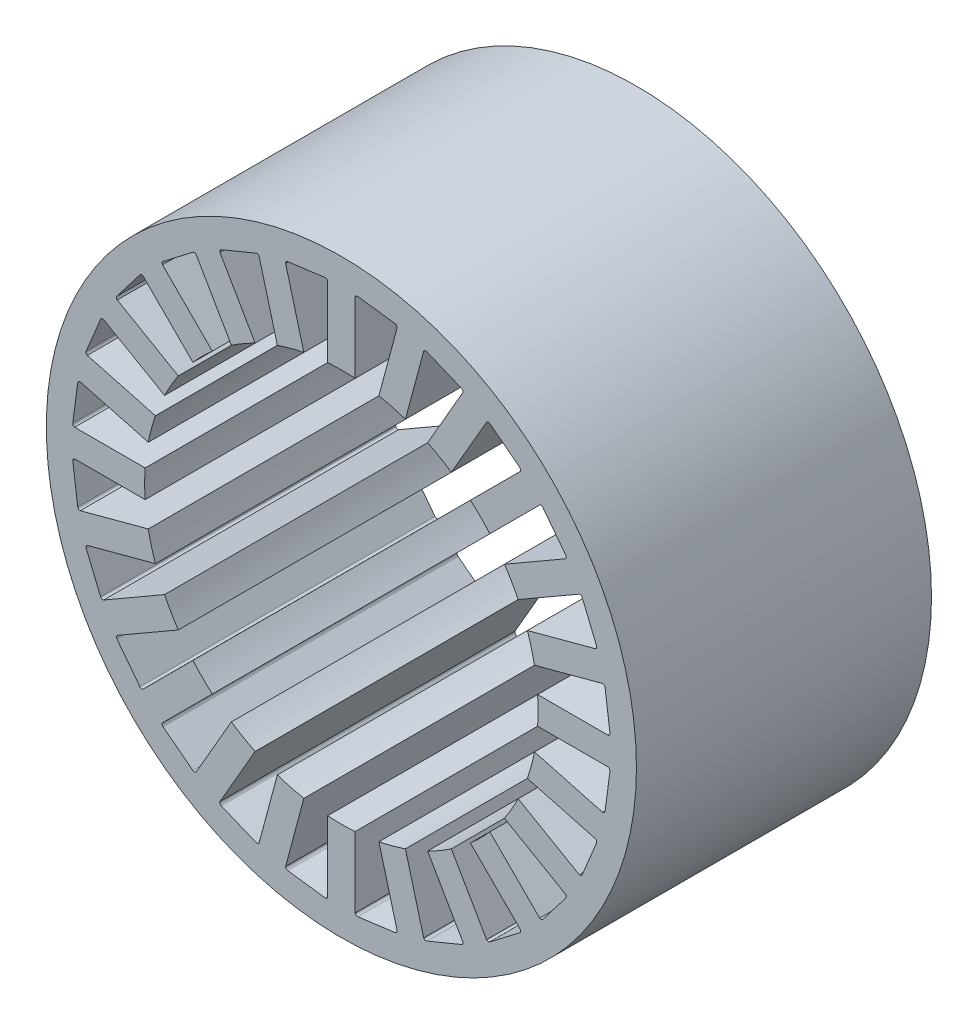
SolidWorks part; units mm, degrees
ref_plane "Ön Düzlem" through (0, 0, 0) normal (0, 0, 1) x (1, 0, 0)
ref_plane "Üst Düzlem" through (0, 0, 0) normal (0, 1, 0) x (1, 0, 0)
ref_plane "Sağ Düzlem" through (0, 0, 0) normal (1, 0, 0) x (0, 0, -1)
sketch "Model" plane through (0, 0, 0) normal (0, 0, 1) x (1, 0, 0)
  line L1 (6.2781, 89.7808) -> (6.2781, 122.029)
  line L2 (7.489, 122.89) -> (24.5724, 120.6409)
  line L3 (25.5193, 119.4959) -> (17.1728, 88.3464)
  line L4 (29.3011, 85.0967) -> (37.6476, 116.2461)
  line L5 (39.0401, 116.7643) -> (54.9593, 110.1703)
  line L6 (55.5775, 108.8193) -> (39.4534, 80.8915)
  line L7 (50.3274, 74.6134) -> (66.4515, 102.5412)
  line L8 (67.9306, 102.6813) -> (81.6008, 92.1919)
  line L9 (81.8483, 90.7268) -> (59.0453, 67.9239)
  line L10 (67.9239, 59.0453) -> (90.7268, 81.8483)
  line L11 (92.1919, 81.6008) -> (102.6813, 67.9306)
  line L12 (102.5412, 66.4515) -> (74.6134, 50.3274)
  line L13 (80.8915, 39.4534) -> (108.8193, 55.5775)
  line L14 (110.1703, 54.9593) -> (116.7643, 39.0401)
  line L15 (116.2461, 37.6476) -> (85.0967, 29.3011)
  line L16 (88.3464, 17.1728) -> (119.4959, 25.5193)
  line L17 (120.6409, 24.5724) -> (122.89, 7.489)
  line L18 (122.029, 6.2781) -> (89.7808, 6.2781)
  line L21 (89.7808, -6.2781) -> (122.029, -6.2781)
  line L22 (122.89, -7.489) -> (120.6409, -24.5724)
  line L23 (119.4959, -25.5193) -> (88.3464, -17.1728)
  line L24 (85.0967, -29.3011) -> (116.2461, -37.6476)
  line L25 (116.7643, -39.0401) -> (110.1703, -54.9593)
  line L26 (108.8193, -55.5775) -> (80.8915, -39.4534)
  line L27 (74.6134, -50.3274) -> (102.5412, -66.4515)
  line L28 (102.6813, -67.9306) -> (92.1919, -81.6008)
  line L29 (90.7268, -81.8483) -> (67.9239, -59.0453)
  line L30 (59.0453, -67.9239) -> (81.8483, -90.7268)
  line L31 (81.6008, -92.1919) -> (67.9306, -102.6813)
  line L32 (66.4515, -102.5412) -> (50.3274, -74.6134)
  line L33 (39.4534, -80.8915) -> (55.5775, -108.8193)
  line L34 (54.9593, -110.1703) -> (39.0401, -116.7643)
  line L35 (37.6476, -116.2461) -> (29.3011, -85.0967)
  line L36 (17.1728, -88.3464) -> (25.5193, -119.4959)
  line L37 (24.5724, -120.6409) -> (7.489, -122.89)
  line L38 (6.2781, -122.029) -> (6.2781, -89.7808)
  line L41 (-6.2781, -89.7808) -> (-6.2781, -122.029)
  line L42 (-7.489, -122.89) -> (-24.5724, -120.6409)
  line L43 (-25.5193, -119.4959) -> (-17.1728, -88.3464)
  line L44 (-29.3011, -85.0967) -> (-37.6476, -116.2461)
  line L45 (-39.0401, -116.7643) -> (-54.9593, -110.1703)
  line L46 (-55.5775, -108.8193) -> (-39.4534, -80.8915)
  line L47 (-50.3274, -74.6134) -> (-66.4515, -102.5412)
  line L48 (-67.9306, -102.6813) -> (-81.6008, -92.1919)
  line L49 (-81.8483, -90.7268) -> (-59.0453, -67.9239)
  line L50 (-67.9239, -59.0453) -> (-90.7268, -81.8483)
  line L51 (-92.1919, -81.6008) -> (-102.6813, -67.9306)
  line L52 (-102.5412, -66.4515) -> (-74.6134, -50.3274)
  line L53 (-80.8915, -39.4534) -> (-108.8193, -55.5775)
  line L54 (-110.1703, -54.9593) -> (-116.7643, -39.0401)
  line L55 (-116.2461, -37.6476) -> (-85.0967, -29.3011)
  line L56 (-88.3464, -17.1728) -> (-119.4959, -25.5193)
  line L57 (-120.6409, -24.5724) -> (-122.89, -7.489)
  line L58 (-122.029, -6.2781) -> (-89.7808, -6.2781)
  line L61 (-89.7808, 6.2781) -> (-122.029, 6.2781)
  line L62 (-122.89, 7.489) -> (-120.6409, 24.5724)
  line L63 (-119.4959, 25.5193) -> (-88.3464, 17.1728)
  line L64 (-85.0967, 29.3011) -> (-116.2461, 37.6476)
  line L65 (-116.7643, 39.0401) -> (-110.1703, 54.9593)
  line L66 (-108.8193, 55.5775) -> (-80.8915, 39.4534)
  line L67 (-74.6134, 50.3274) -> (-102.5412, 66.4515)
  line L68 (-102.6813, 67.9306) -> (-92.1919, 81.6008)
  line L69 (-90.7268, 81.8483) -> (-67.9239, 59.0453)
  line L70 (-59.0453, 67.9239) -> (-81.8483, 90.7268)
  line L71 (-81.6008, 92.1919) -> (-67.9306, 102.6813)
  line L72 (-66.4515, 102.5412) -> (-50.3274, 74.6134)
  line L73 (-39.4534, 80.8915) -> (-55.5775, 108.8193)
  line L74 (-54.9593, 110.1703) -> (-39.0401, 116.7643)
  line L75 (-37.6476, 116.2461) -> (-29.3011, 85.0967)
  line L76 (-17.1728, 88.3464) -> (-25.5193, 119.4959)
  line L77 (-24.5724, 120.6409) -> (-7.489, 122.89)
  line L78 (-6.2781, 122.029) -> (-6.2781, 89.7808)
  arc A1 (6.2781, 89.7808) -> (0, 90) centre (0, 0) ccw
  arc A2 (7.489, 122.89) -> (6.2781, 122.029) centre (7.3769, 121.7655) ccw
  arc A3 (25.5193, 119.4959) -> (24.5724, 120.6409) centre (24.3897, 119.5258) ccw
  arc A4 (29.3011, 85.0967) -> (17.1728, 88.3464) centre (0, 0) ccw
  arc A5 (39.0401, 116.7643) -> (37.6476, 116.2461) centre (38.6408, 115.7072) ccw
  arc A6 (55.5775, 108.8193) -> (54.9593, 110.1703) centre (54.4942, 109.1405) ccw
  arc A7 (50.3274, 74.6134) -> (39.4534, 80.8915) centre (0, 0) ccw
  arc A8 (67.9306, 102.6813) -> (66.4515, 102.5412) centre (67.2714, 101.7636) ccw
  arc A9 (81.8483, 90.7268) -> (81.6008, 92.1919) centre (80.885, 91.3175) ccw
  arc A10 (67.9239, 59.0453) -> (59.0453, 67.9239) centre (0, 0) ccw
  arc A11 (92.1919, 81.6008) -> (90.7268, 81.8483) centre (91.3175, 80.885) ccw
  arc A12 (102.5412, 66.4515) -> (102.6813, 67.9306) centre (101.7636, 67.2714) ccw
  arc A13 (80.8915, 39.4534) -> (74.6134, 50.3274) centre (0, 0) ccw
  arc A14 (110.1703, 54.9593) -> (108.8193, 55.5775) centre (109.1405, 54.4942) ccw
  arc A15 (116.2461, 37.6476) -> (116.7643, 39.0401) centre (115.7072, 38.6408) ccw
  arc A16 (88.3464, 17.1728) -> (85.0967, 29.3011) centre (0, 0) ccw
  arc A17 (120.6409, 24.5724) -> (119.4959, 25.5193) centre (119.5258, 24.3897) ccw
  arc A18 (122.029, 6.2781) -> (122.89, 7.489) centre (121.7655, 7.3769) ccw
  arc A19 (90, 0) -> (89.7808, 6.2781) centre (0, 0) ccw
  arc A21 (89.7808, -6.2781) -> (90, 0) centre (0, 0) ccw
  arc A22 (122.89, -7.489) -> (122.029, -6.2781) centre (121.7655, -7.3769) ccw
  arc A23 (119.4959, -25.5193) -> (120.6409, -24.5724) centre (119.5258, -24.3897) ccw
  arc A24 (85.0967, -29.3011) -> (88.3464, -17.1728) centre (0, 0) ccw
  arc A25 (116.7643, -39.0401) -> (116.2461, -37.6476) centre (115.7072, -38.6408) ccw
  arc A26 (108.8193, -55.5775) -> (110.1703, -54.9593) centre (109.1405, -54.4942) ccw
  arc A27 (74.6134, -50.3274) -> (80.8915, -39.4534) centre (0, 0) ccw
  arc A28 (102.6813, -67.9306) -> (102.5412, -66.4515) centre (101.7636, -67.2714) ccw
  arc A29 (90.7268, -81.8483) -> (92.1919, -81.6008) centre (91.3175, -80.885) ccw
  arc A30 (59.0453, -67.9239) -> (67.9239, -59.0453) centre (0, 0) ccw
  arc A31 (81.6008, -92.1919) -> (81.8483, -90.7268) centre (80.885, -91.3175) ccw
  arc A32 (66.4515, -102.5412) -> (67.9306, -102.6813) centre (67.2714, -101.7636) ccw
  arc A33 (39.4534, -80.8915) -> (50.3274, -74.6134) centre (0, 0) ccw
  arc A34 (54.9593, -110.1703) -> (55.5775, -108.8193) centre (54.4942, -109.1405) ccw
  arc A35 (37.6476, -116.2461) -> (39.0401, -116.7643) centre (38.6408, -115.7072) ccw
  arc A36 (17.1728, -88.3464) -> (29.3011, -85.0967) centre (0, 0) ccw
  arc A37 (24.5724, -120.6409) -> (25.5193, -119.4959) centre (24.3897, -119.5258) ccw
  arc A38 (6.2781, -122.029) -> (7.489, -122.89) centre (7.3769, -121.7655) ccw
  arc A39 (0, -90) -> (6.2781, -89.7808) centre (0, 0) ccw
  arc A41 (-6.2781, -89.7808) -> (0, -90) centre (0, 0) ccw
  arc A42 (-7.489, -122.89) -> (-6.2781, -122.029) centre (-7.3769, -121.7655) ccw
  arc A43 (-25.5193, -119.4959) -> (-24.5724, -120.6409) centre (-24.3897, -119.5258) ccw
  arc A44 (-29.3011, -85.0967) -> (-17.1728, -88.3464) centre (0, 0) ccw
  arc A45 (-39.0401, -116.7643) -> (-37.6476, -116.2461) centre (-38.6408, -115.7072) ccw
  arc A46 (-55.5775, -108.8193) -> (-54.9593, -110.1703) centre (-54.4942, -109.1405) ccw
  arc A47 (-50.3274, -74.6134) -> (-39.4534, -80.8915) centre (0, 0) ccw
  arc A48 (-67.9306, -102.6813) -> (-66.4515, -102.5412) centre (-67.2714, -101.7636) ccw
  arc A49 (-81.8483, -90.7268) -> (-81.6008, -92.1919) centre (-80.885, -91.3175) ccw
  arc A50 (-67.9239, -59.0453) -> (-59.0453, -67.9239) centre (0, 0) ccw
  arc A51 (-92.1919, -81.6008) -> (-90.7268, -81.8483) centre (-91.3175, -80.885) ccw
  arc A52 (-102.5412, -66.4515) -> (-102.6813, -67.9306) centre (-101.7636, -67.2714) ccw
  arc A53 (-80.8915, -39.4534) -> (-74.6134, -50.3274) centre (0, 0) ccw
  arc A54 (-110.1703, -54.9593) -> (-108.8193, -55.5775) centre (-109.1405, -54.4942) ccw
  arc A55 (-116.2461, -37.6476) -> (-116.7643, -39.0401) centre (-115.7072, -38.6408) ccw
  arc A56 (-88.3464, -17.1728) -> (-85.0967, -29.3011) centre (0, 0) ccw
  arc A57 (-120.6409, -24.5724) -> (-119.4959, -25.5193) centre (-119.5258, -24.3897) ccw
  arc A58 (-122.029, -6.2781) -> (-122.89, -7.489) centre (-121.7655, -7.3769) ccw
  arc A59 (-90, 0) -> (-89.7808, -6.2781) centre (0, 0) ccw
  arc A61 (-89.7808, 6.2781) -> (-90, 0) centre (0, 0) ccw
  arc A62 (-122.89, 7.489) -> (-122.029, 6.2781) centre (-121.7655, 7.3769) ccw
  arc A63 (-119.4959, 25.5193) -> (-120.6409, 24.5724) centre (-119.5258, 24.3897) ccw
  arc A64 (-85.0967, 29.3011) -> (-88.3464, 17.1728) centre (0, 0) ccw
  arc A65 (-116.7643, 39.0401) -> (-116.2461, 37.6476) centre (-115.7072, 38.6408) ccw
  arc A66 (-108.8193, 55.5775) -> (-110.1703, 54.9593) centre (-109.1405, 54.4942) ccw
  arc A67 (-74.6134, 50.3274) -> (-80.8915, 39.4534) centre (0, 0) ccw
  arc A68 (-102.6813, 67.9306) -> (-102.5412, 66.4515) centre (-101.7636, 67.2714) ccw
  arc A69 (-90.7268, 81.8483) -> (-92.1919, 81.6008) centre (-91.3175, 80.885) ccw
  arc A70 (-59.0453, 67.9239) -> (-67.9239, 59.0453) centre (0, 0) ccw
  arc A71 (-81.6008, 92.1919) -> (-81.8483, 90.7268) centre (-80.885, 91.3175) ccw
  arc A72 (-66.4515, 102.5412) -> (-67.9306, 102.6813) centre (-67.2714, 101.7636) ccw
  arc A73 (-39.4534, 80.8915) -> (-50.3274, 74.6134) centre (0, 0) ccw
  arc A74 (-54.9593, 110.1703) -> (-55.5775, 108.8193) centre (-54.4942, 109.1405) ccw
  arc A75 (-37.6476, 116.2461) -> (-39.0401, 116.7643) centre (-38.6408, 115.7072) ccw
  arc A76 (-17.1728, 88.3464) -> (-29.3011, 85.0967) centre (0, 0) ccw
  arc A77 (-24.5724, 120.6409) -> (-25.5193, 119.4959) centre (-24.3897, 119.5258) ccw
  arc A78 (-6.2781, 122.029) -> (-7.489, 122.89) centre (-7.3769, 121.7655) ccw
  arc A79 (0, 90) -> (-6.2781, 89.7808) centre (0, 0) ccw
  circle A80 centre (0, 0) radius 135
  point P212 (0, 0)
  dimension "D2" = 270
  dimension "D1" = 4
extrude "Boss-Extrude1" add sketch "Model" along normal blind 135
